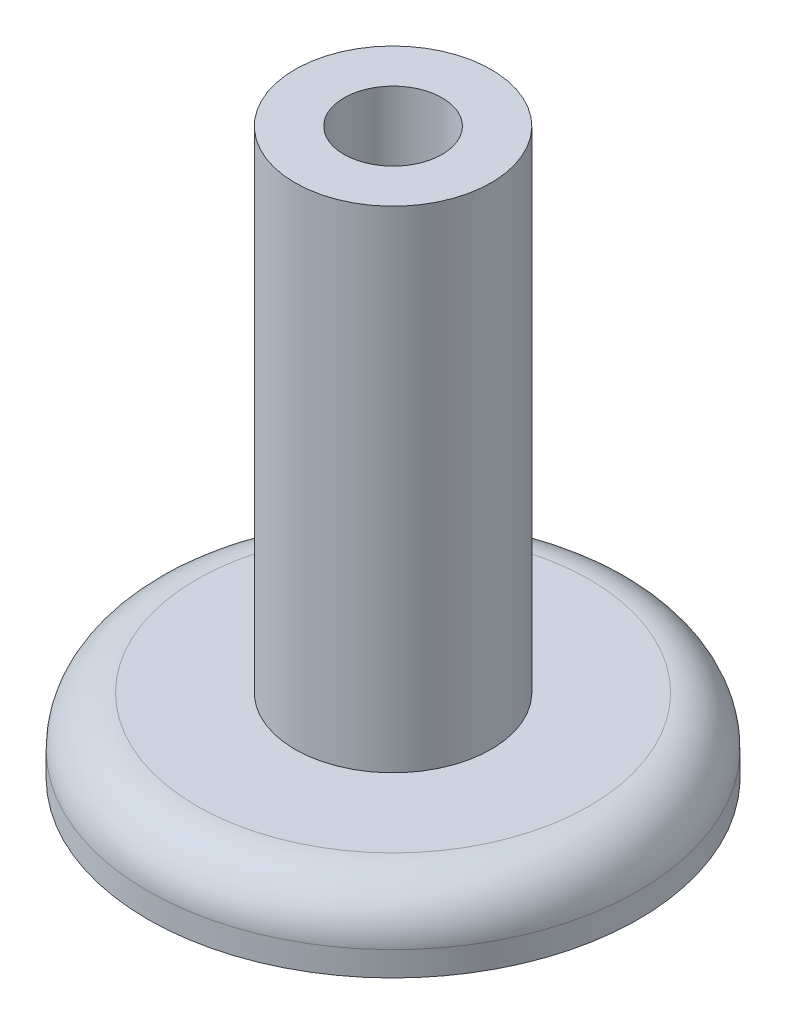
SolidWorks part; units mm, degrees
ref_plane "Спереди" through (0, 0, 0) normal (0, 0, 1) x (1, 0, 0)
ref_plane "Сверху" through (0, 0, 0) normal (0, 1, 0) x (1, 0, 0)
ref_plane "Справа" through (0, 0, 0) normal (1, 0, 0) x (0, 0, -1)
sketch "Эскиз1" plane through (0, 0, 0) normal (0, 1, 0) x (1, 0, 0)
  circle A0 centre (0, 0) radius 5
  circle A1 centre (0, 0) radius 1
  dimension "D1" = 10
  dimension "D2" = 2
extrude "Бобышка-Вытянуть1" add sketch "Эскиз1" along normal blind 1.5
fillet "Скругление1" radius 1 1 edges at (0, 1.5, 5)
sketch "Эскиз2" plane through (0, 1.5, 0) normal (0, 1, 0) x (1, 0, 0)
  circle A0 centre (0, 0) radius 2
  circle A1 centre (0, 0) radius 1 construction
  circle A2 centre (0, 0) radius 1
  dimension "D1" = 4
extrude "Бобышка-Вытянуть2" add sketch "Эскиз2" along normal blind 10
